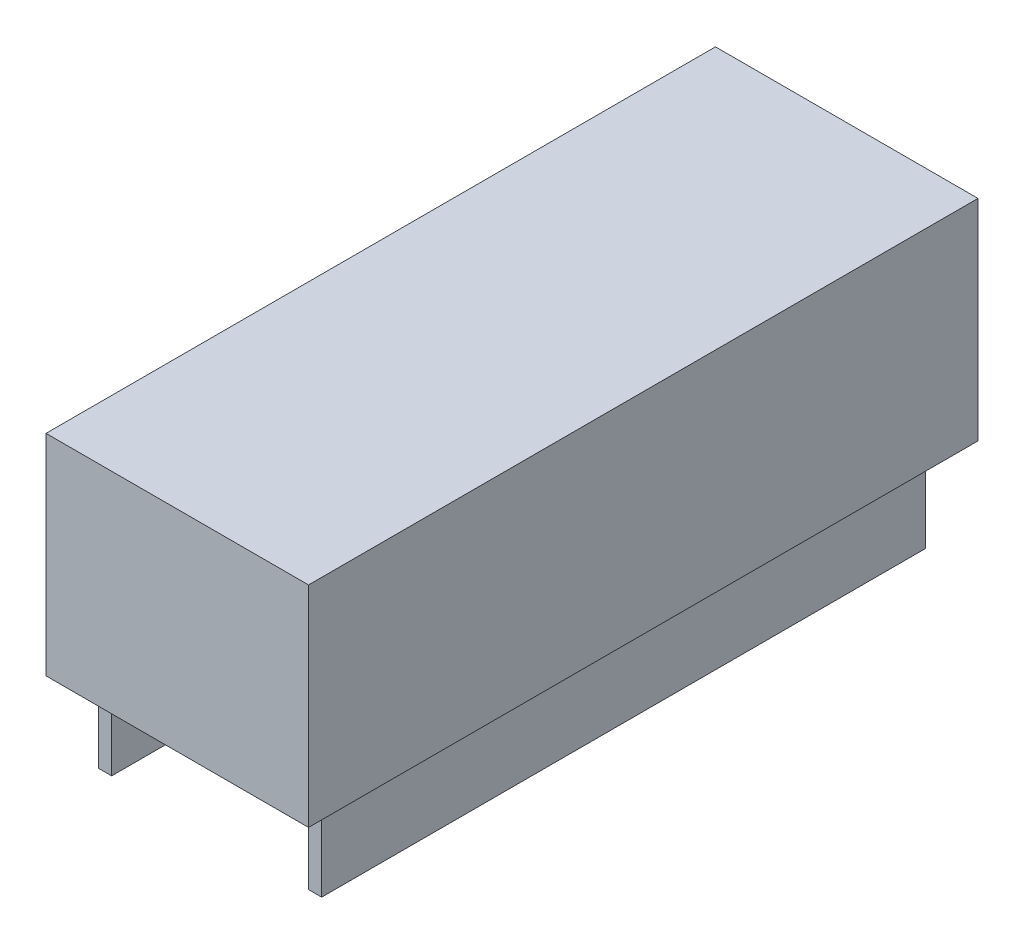
SolidWorks part; units mm, degrees
ref_plane "Front Plane" through (0, 0, 0) normal (0, 0, 1) x (1, 0, 0)
ref_plane "Top Plane" through (0, 0, 0) normal (0, 1, 0) x (1, 0, 0)
ref_plane "Right Plane" through (0, 0, 0) normal (1, 0, 0) x (0, 0, -1)
sketch "Sketch1" plane through (0, 0, 0) normal (0, 1, 0) x (1, 0, 0)
  line L1 (-5, -12.75) -> (5, -12.75)
  line L2 (-5, -12.75) -> (-5, 12.75)
  line L3 (-5, 12.75) -> (5, 12.75)
  line L4 (5, -12.75) -> (5, 12.75)
  line L5 (-5, -12.75) -> (5, 12.75) construction
  line L6 (-5, 12.75) -> (5, -12.75) construction
  point P0 (0, 0)
  dimension "D1" = 10
  dimension "D2" = 25.5
extrude "Boss-Extrude1" add sketch "Sketch1" against normal blind 8
sketch "Sketch2" plane through (0, -8, 0) normal (0, -1, 0) x (1, 0, 0)
  line L0 (0, -4.4) -> (0, 4.4) construction
  line L1 (4.25, 11.5) -> (3.75, 11.5)
  line L2 (4.25, 11.5) -> (4.25, -11.5)
  line L3 (4.25, -11.5) -> (3.75, -11.5)
  line L4 (3.75, 11.5) -> (3.75, -11.5)
  line L5 (4.25, 11.5) -> (3.75, -11.5) construction
  line L6 (4.25, -11.5) -> (3.75, 11.5) construction
  line L7 (-4.25, -11.5) -> (-3.75, 11.5) construction
  line L8 (-4.25, 11.5) -> (-3.75, -11.5) construction
  line L9 (-3.75, 11.5) -> (-3.75, -11.5)
  line L10 (-4.25, -11.5) -> (-3.75, -11.5)
  line L11 (-4.25, 11.5) -> (-4.25, -11.5)
  line L12 (-4.25, 11.5) -> (-3.75, 11.5)
  point P0 (4, 0)
  point P5 (0, 0)
  point P13 (-4, 0)
  dimension "D1" = 0.5
  dimension "D2" = 23
  dimension "D3" = 4
extrude "Boss-Extrude2" add sketch "Sketch2" along normal blind 3.3
